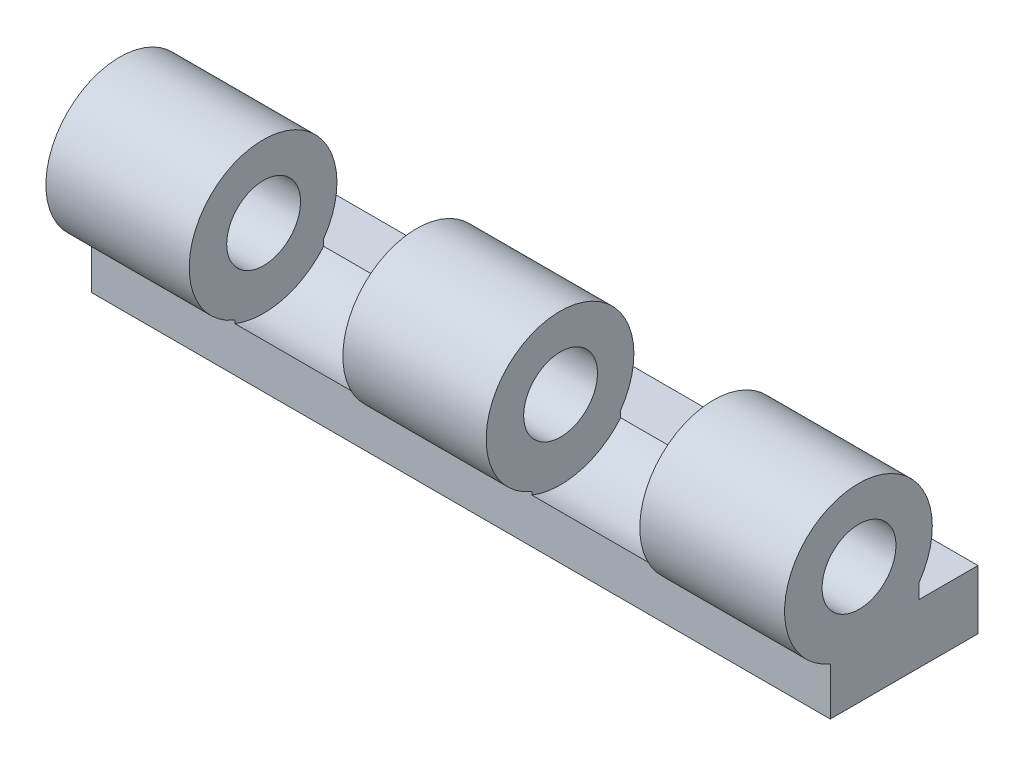
SolidWorks part; units mm, degrees
ref_plane "Front Plane" through (0, 0, 0) normal (0, 0, 1) x (1, 0, 0)
ref_plane "Top Plane" through (0, 0, 0) normal (0, 1, 0) x (1, 0, 0)
ref_plane "Right Plane" through (0, 0, 0) normal (1, 0, 0) x (0, 0, -1)
sketch "Sketch1" plane through (0, 0, 0) normal (0, 0, 1) x (1, 0, 0)
  line L1 (0, 0) -> (220, 0)
  line L2 (0, 0) -> (0, 10)
  line L3 (0, 10) -> (220, 10)
  line L4 (220, 0) -> (220, 10)
  line L5 (-15, 0) -> (235, 0)
  line L6 (-15, 0) -> (-15, 25)
  line L7 (-15, 25) -> (235, 25)
  line L8 (235, 0) -> (235, 25)
extrude "Boss-Extrude1" add sketch "Sketch1" along normal blind 50 contours L7 L8 L5 L6
sketch "Sketch2" plane through (0, 0, 0) normal (0, 0, -1) x (-1, 0, 0)
  line L1 (0, 0) -> (-220, 0)
  line L2 (0, 0) -> (0, 10)
  line L3 (0, 10) -> (-220, 10)
  line L4 (-220, 0) -> (-220, 10)
extrude "Cut-Extrude1" cut sketch "Sketch2" against normal blind 35
sketch "Sketch3" plane through (-15, 0, 0) normal (-1, 0, 0) x (0, 0, 1)
  circle A0 centre (40.462, 39.2818) radius 25
  dimension "D1" = 50
extrude "Boss-Extrude2" add sketch "Sketch3" against normal blind 49
pattern_linear "LPattern1" count 3 spacing 100.5 along (1, 0, 0) of "Boss-Extrude2"
sketch "Sketch7" plane through (-15, 0, 0) normal (-1, 0, 0) x (0, 0, 1)
  circle A0 centre (40.2725, 39.7924) radius 12.5
  point P2 (713.5901, -249.5384)
extrude "Cut-Extrude2" cut sketch "Sketch7" against normal blind 250 contours A0
sketch "Sketch8" plane through (0, 25, 0) normal (0, 1, 0) x (1, 0, 0)
  line L1 (-15, -19.943) -> (235, -19.943)
  line L2 (-15, -19.943) -> (-15, 0)
  line L3 (-15, 0) -> (235, 0)
  line L4 (235, -19.943) -> (235, 0)
extrude "Cut-Extrude3" cut sketch "Sketch8" against normal blind 5
sketch "Sketch10" plane through (85.5, 0, 0) normal (-1, 0, 0) x (0, 0, 1)
  circle A0 centre (40.2725, 39.7924) radius 26.5
extrude "Cut-Extrude4" cut sketch "Sketch10" along normal blind 52
ref_plane "Plane1" through (110, 0, 0) normal (-1, 0, 0) x (0, 0, 1)
sketch "Sketch15" plane through (186, 0, 0) normal (-1, 0, 0) x (0, 0, 1)
  circle A0 centre (40.2725, 39.7924) radius 26.5
extrude "Cut-Extrude5" cut sketch "Sketch15" along normal blind 52
